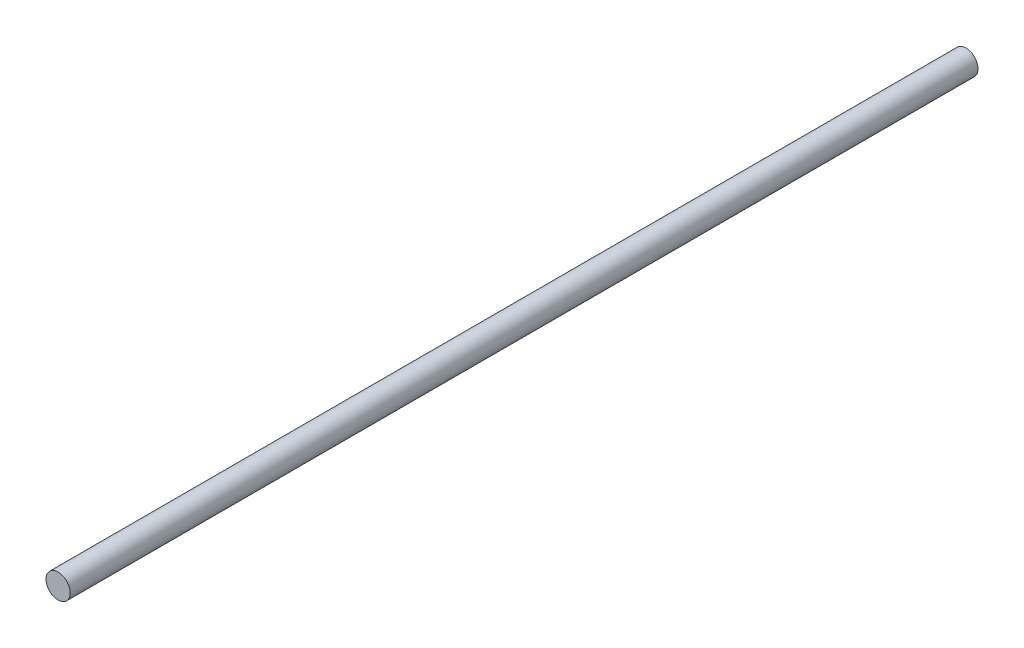
SolidWorks part; units mm, degrees
material "普通碳钢"
ref_plane "前视" through (0, 0, 0) normal (0, 0, 1) x (1, 0, 0)
ref_plane "上视" through (0, 0, 0) normal (0, 1, 0) x (1, 0, 0)
ref_plane "右视" through (0, 0, 0) normal (1, 0, 0) x (0, 0, -1)
sketch "草图1" plane through (0, 0, 0) normal (0, 0, 1) x (1, 0, 0)
  circle A0 centre (0, 0) radius 1
  dimension "D1" = 2
extrude "凸台-拉伸1" add sketch "草图1" along normal mid plane 75
